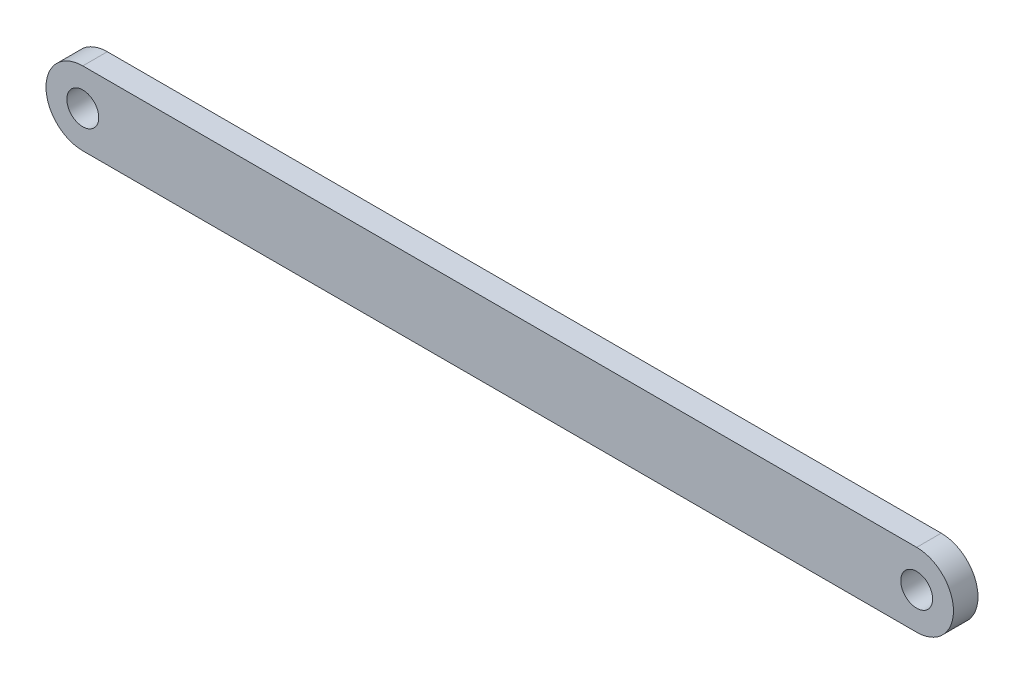
SolidWorks part; units mm, degrees
ref_plane "Front Plane" through (0, 0, 0) normal (0, 0, 1) x (1, 0, 0)
ref_plane "Top Plane" through (0, 0, 0) normal (0, 1, 0) x (1, 0, 0)
ref_plane "Right Plane" through (0, 0, 0) normal (1, 0, 0) x (0, 0, -1)
sketch "Sketch1" plane through (0, 0, 0) normal (0, 0, 1) x (1, 0, 0)
  line L0 (0, 0) -> (170, 0) construction
  line L1 (0, 7.5) -> (170, 7.5)
  line L2 (0, -7.5) -> (170, -7.5)
  arc A0 (0, 7.5) -> (0, -7.5) centre (0, 0) ccw
  arc A1 (170, -7.5) -> (170, 7.5) centre (170, 0) ccw
  circle A2 centre (0, 0) radius 3.25
  circle A3 centre (170, 0) radius 3.25
  point P3 (85, 0)
  dimension "D2" = 6.5
  dimension "D3" = 7.5
  dimension "D1" = 170
extrude "Boss-Extrude1" add sketch "Sketch1" along normal mid plane 5
